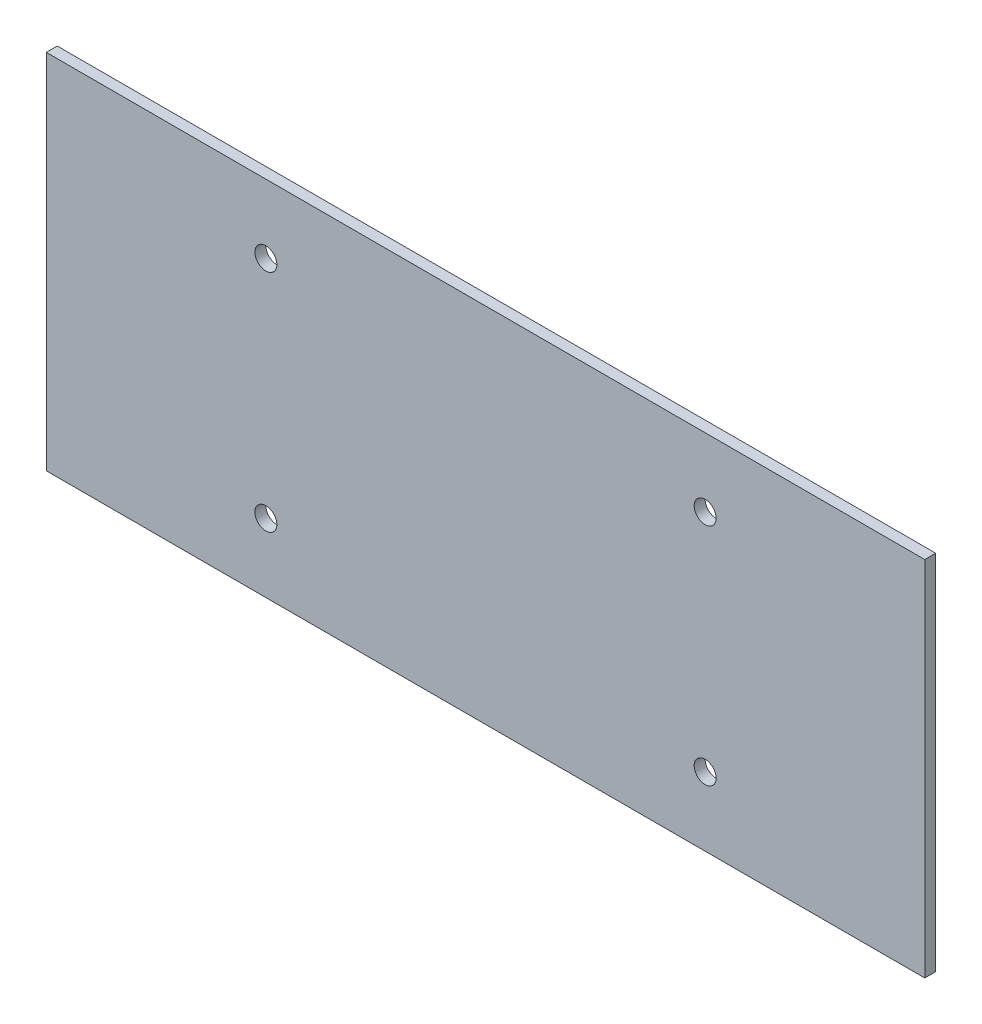
SolidWorks part; units mm, degrees
ref_plane "Ön Düzlem" through (0, 0, 0) normal (0, 0, 1) x (1, 0, 0)
ref_plane "Üst Düzlem" through (0, 0, 0) normal (0, 1, 0) x (1, 0, 0)
ref_plane "Sağ Düzlem" through (0, 0, 0) normal (1, 0, 0) x (0, 0, -1)
sketch "Sketch1" plane through (0, 0, 0) normal (0, 0, 1) x (1, 0, 0)
  line L1 (0, 0) -> (160, 0)
  line L2 (0, 0) -> (0, 66)
  line L3 (0, 66) -> (160, 66)
  line L4 (160, 0) -> (160, 66)
extrude "Boss-Extrude1" add sketch "Sketch1" along normal blind 2
sketch "Sketch2" plane through (0, 0, 2) normal (0, 0, 1) x (1, 0, 0)
  line L0 (160, 66) -> (0, 66) construction
  line L1 (0, 66) -> (0, 0) construction
  line L2 (160, 0) -> (160, 66) construction
  line L3 (0, 0) -> (160, 0) construction
  circle A0 centre (40, 53.5) radius 2
  circle A1 centre (120, 53.5) radius 2
  circle A2 centre (40, 12.5) radius 2
  circle A3 centre (120, 12.5) radius 2
  dimension "D1" = 12.5
  dimension "D3" = 40
  dimension "D5" = 40
  dimension "D7" = 40
  dimension "D8" = 12.5
  dimension "D2" = 40
  dimension "D4" = 12.5
  dimension "D6" = 12.5
extrude "Cut-Extrude1" cut sketch "Sketch2" against normal through all
